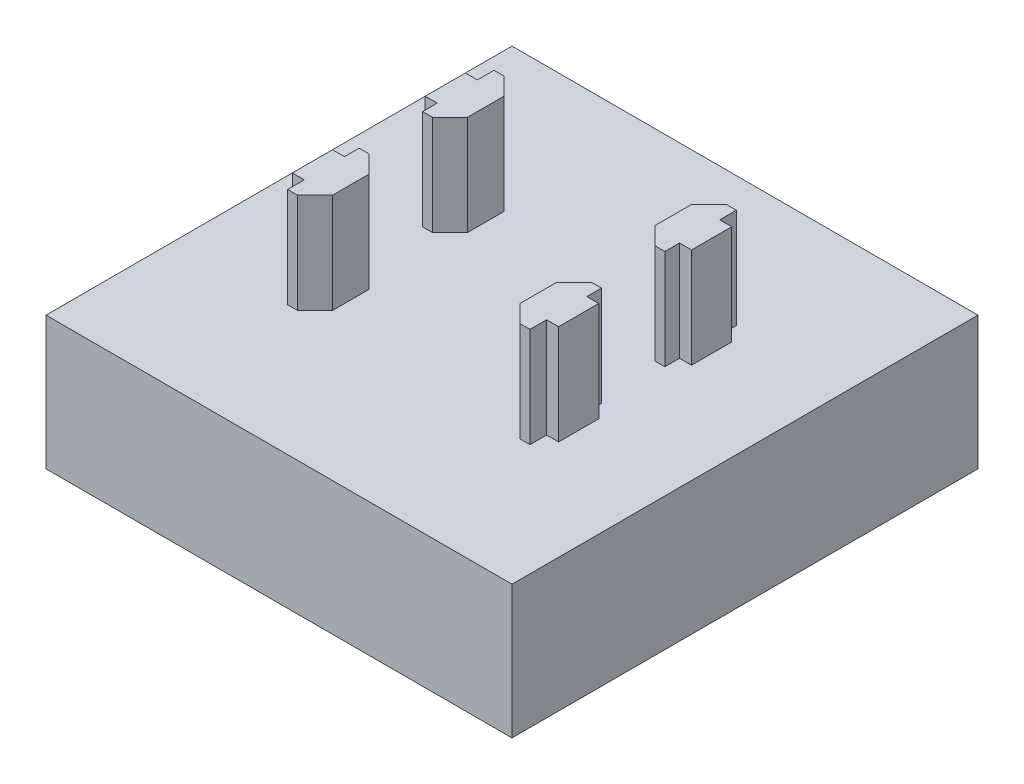
SolidWorks part; units mm, degrees
ref_plane "Front Plane" through (0, 0, 0) normal (0, 0, 1) x (1, 0, 0)
ref_plane "Top Plane" through (0, 0, 0) normal (0, 1, 0) x (1, 0, 0)
ref_plane "Right Plane" through (0, 0, 0) normal (1, 0, 0) x (0, 0, -1)
sketch "Sketch1" plane through (0, 0, 0) normal (0, 1, 0) x (1, 0, 0)
  line L1 (0, 0) -> (-70, 0)
  line L2 (0, 0) -> (0, -70)
  line L3 (0, -70) -> (-70, -70)
  line L4 (-70, 0) -> (-70, -70)
  dimension "D1" = 70
  dimension "D2" = 70
extrude "Boss-Extrude1" add sketch "Sketch1" along normal blind 20
sketch "Sketch2" plane through (0, 20, 0) normal (0, 1, 0) x (1, 0, 0)
  line L0 (-55, -22) -> (-53.2, -22)
  line L2 (-53.2, -22) -> (-53.2, -19.5)
  line L3 (-53.2, -19.5) -> (-51.7, -19.5)
  line L4 (-51.7, -19.5) -> (-49.0837, -22.1163)
  line L5 (-49.0837, -22.1163) -> (-49.0837, -27.6163)
  line L6 (-49.0837, -27.6163) -> (-51.7, -30.2326)
  line L7 (-51.7, -30.2326) -> (-53.2, -30.2326)
  line L8 (-53.2, -30.2326) -> (-53.2, -28.0326)
  line L9 (-53.2, -28.0326) -> (-55, -28.0326)
  line L10 (-55, -28.0326) -> (-55, -22)
  line L11 (0, 0) -> (-70, 0) construction
  line L12 (-70, 0) -> (-70, -70) construction
  line L13 (-35, 0) -> (-35, -70) construction
  line L14 (-70, -70) -> (0, -70) construction
  line L15 (-70, -35) -> (0, -35) construction
  line L16 (0, -70) -> (0, 0) construction
  line L18 (-16.8, -28.0326) -> (-15, -28.0326)
  line L19 (-16.8, -30.2326) -> (-16.8, -28.0326)
  line L20 (-18.3, -30.2326) -> (-16.8, -30.2326)
  line L21 (-20.9163, -27.6163) -> (-18.3, -30.2326)
  line L22 (-20.9163, -22.1163) -> (-20.9163, -27.6163)
  line L23 (-18.3, -19.5) -> (-20.9163, -22.1163)
  line L24 (-16.8, -19.5) -> (-18.3, -19.5)
  line L25 (-16.8, -22) -> (-16.8, -19.5)
  line L26 (-15, -22) -> (-16.8, -22)
  line L27 (-15, -28.0326) -> (-15, -22)
  line L28 (-53.2, -41.9674) -> (-55, -41.9674)
  line L29 (-53.2, -39.7674) -> (-53.2, -41.9674)
  line L30 (-51.7, -39.7674) -> (-53.2, -39.7674)
  line L31 (-49.0837, -42.3837) -> (-51.7, -39.7674)
  line L32 (-49.0837, -47.8837) -> (-49.0837, -42.3837)
  line L33 (-51.7, -50.5) -> (-49.0837, -47.8837)
  line L34 (-53.2, -50.5) -> (-51.7, -50.5)
  line L35 (-53.2, -48) -> (-53.2, -50.5)
  line L36 (-55, -48) -> (-53.2, -48)
  line L37 (-55, -41.9674) -> (-55, -48)
  line L38 (-16.8, -39.7674) -> (-16.8, -41.9674)
  line L39 (-18.3, -39.7674) -> (-16.8, -39.7674)
  line L40 (-20.9163, -42.3837) -> (-18.3, -39.7674)
  line L41 (-20.9163, -47.8837) -> (-20.9163, -42.3837)
  line L42 (-18.3, -50.5) -> (-20.9163, -47.8837)
  line L43 (-16.8, -50.5) -> (-18.3, -50.5)
  line L44 (-16.8, -48) -> (-16.8, -50.5)
  line L45 (-15, -48) -> (-16.8, -48)
  line L46 (-15, -41.9674) -> (-15, -48)
  line L47 (-16.8, -41.9674) -> (-15, -41.9674)
  dimension "D1" = 1.8
  dimension "D2" = 1.8
  dimension "D3" = 2.5
  dimension "D4" = 2.2
  dimension "D5" = 3.7
  dimension "D6" = 3.7
  dimension "D7" = 5.5
  dimension "D8" = 1.5
  dimension "D9" = 1.5
  dimension "D10" = 19.5
  dimension "D11" = 15
extrude "Boss-Extrude3" add sketch "Sketch2" along normal blind 15
